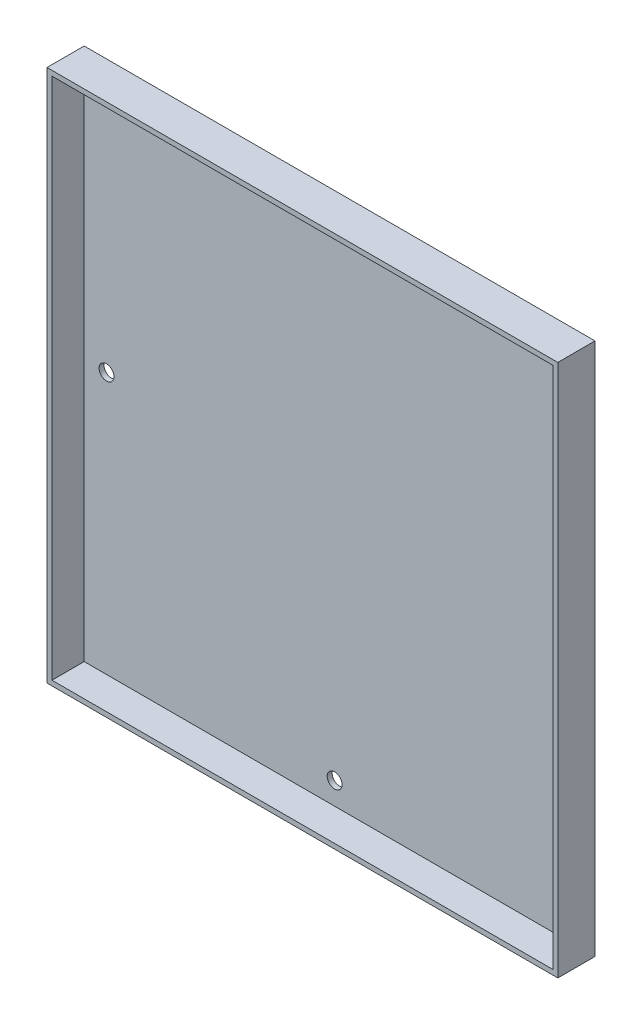
SolidWorks part; units mm, degrees
ref_plane "前视基准面" through (0, 0, 0) normal (0, 0, 1) x (1, 0, 0)
ref_plane "上视基准面" through (0, 0, 0) normal (0, 1, 0) x (1, 0, 0)
ref_plane "右视基准面" through (0, 0, 0) normal (1, 0, 0) x (0, 0, -1)
sketch "草图1" plane through (0, 0, 0) normal (0, 0, 1) x (1, 0, 0)
  line L1 (0, 0) -> (206, 0)
  line L2 (0, 0) -> (0, -215)
  line L3 (0, -215) -> (206, -215)
  line L4 (206, 0) -> (206, -215)
  dimension "D1" = 206
  dimension "D2" = 215
extrude "拉伸1" add sketch "草图1" along normal blind 15
shell "抽壳1" thickness 2
sketch "草图2" plane through (0, 0, 0) normal (0, 0, -1) x (-1, 0, 0)
  circle A0 centre (-103, -11) radius 3
  circle A1 centre (-195, -107.5) radius 3
  circle A2 centre (-11, -107.5) radius 3
  circle A3 centre (-103, -204) radius 3
extrude "切除-拉伸1" cut sketch "草图2" against normal blind 10
